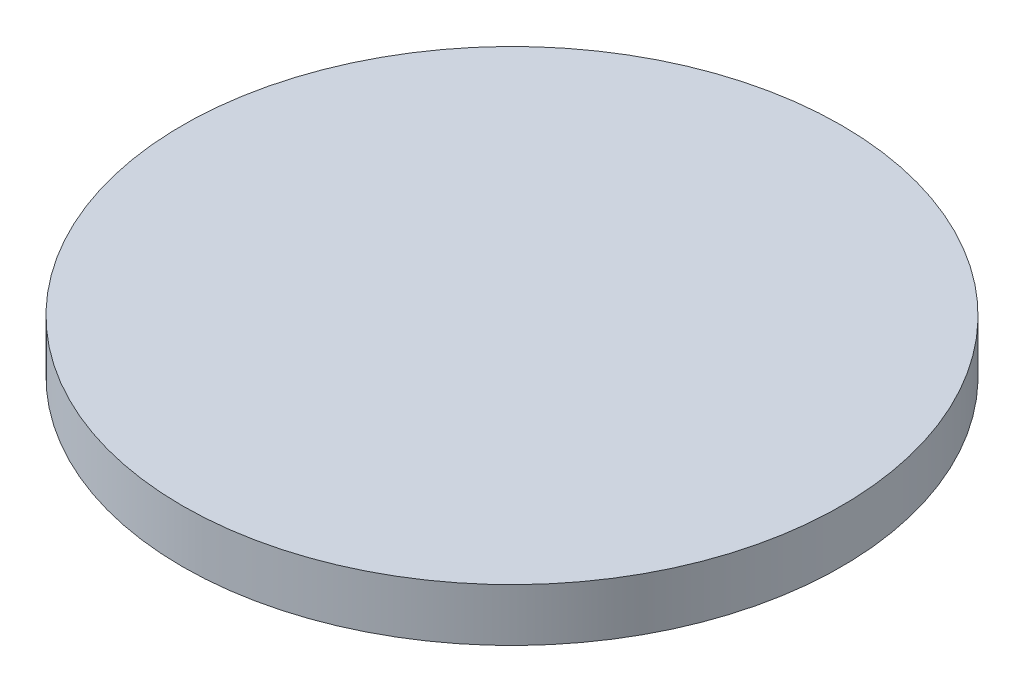
SolidWorks part; units mm, degrees
ref_plane "Front Plane" through (0, 0, 0) normal (0, 0, 1) x (1, 0, 0)
ref_plane "Top Plane" through (0, 0, 0) normal (0, 1, 0) x (1, 0, 0)
ref_plane "Right Plane" through (0, 0, 0) normal (1, 0, 0) x (0, 0, -1)
sketch "Sketch1" plane through (0, 0, 0) normal (0, 1, 0) x (1, 0, 0)
  circle A0 centre (0, 0) radius 10
extrude "Boss-Extrude1" add sketch "Sketch1" along normal blind 1.6
